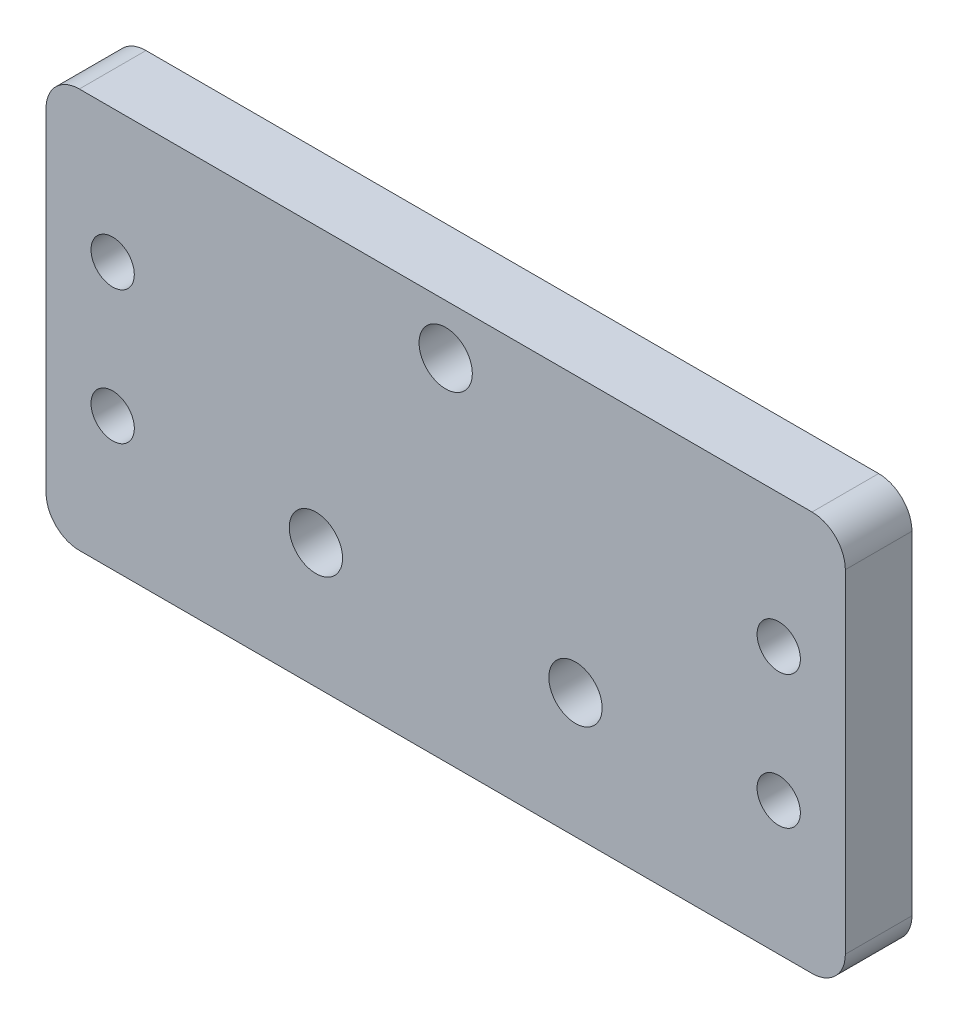
SolidWorks part; units mm, degrees
ref_plane "正面" through (0, 0, 0) normal (0, 0, 1) x (1, 0, 0)
ref_plane "平面" through (0, 0, 0) normal (0, 1, 0) x (1, 0, 0)
ref_plane "右側面" through (0, 0, 0) normal (1, 0, 0) x (0, 0, -1)
sketch "ｽｹｯﾁ1" plane through (0, 0, 0) normal (0, 0, 1) x (1, 0, 0)
  line L1 (0, 0) -> (120, 0)
  line L2 (0, 0) -> (0, 60)
  line L3 (0, 60) -> (120, 60)
  line L4 (120, 0) -> (120, 60)
  dimension "D1" = 60
  dimension "D2" = 120
extrude "ﾎﾞｽ - 押し出し1" add sketch "ｽｹｯﾁ1" along normal blind 10
sketch "ｽｹｯﾁ2" plane through (0, 0, 10) normal (0, 0, 1) x (1, 0, 0)
  line L0 (0, 30) -> (120, 30) construction
  line L1 (0, 60) -> (0, 0) construction
  line L2 (120, 0) -> (120, 60) construction
  line L3 (60, 0) -> (60, 60) construction
  line L4 (0, 0) -> (120, 0) construction
  line L5 (120, 60) -> (0, 60) construction
  circle A0 centre (10, 40) radius 3.25
  circle A1 centre (110, 40) radius 3.25
  circle A3 centre (110, 20) radius 3.25
  circle A4 centre (10, 20) radius 3.25
  point P18 (10.2137, 30)
  dimension "D4" = 6.5
  dimension "D1" = 10
  dimension "D2" = 10
  dimension "D3" = 10
  dimension "D5" = 10
extrude "ｶｯﾄ - 押し出し1" cut sketch "ｽｹｯﾁ2" against normal through all
sketch "ｽｹｯﾁ3" plane through (0, 0, 10) normal (0, 0, 1) x (1, 0, 0)
  line L0 (60, 0) -> (60, 60) construction
  line L1 (0, 0) -> (120, 0) construction
  line L2 (120, 60) -> (0, 60) construction
  line L3 (120, 30) -> (0, 30) construction
  line L4 (120, 0) -> (120, 60) construction
  line L5 (0, 60) -> (0, 0) construction
  line L6 (60, 30) -> (79.4856, 18.75) construction
  circle A0 centre (60, 52.5) radius 2.25
  circle A1 centre (79.4856, 18.75) radius 2.25
  circle A2 centre (40.5144, 18.75) radius 2.25
  point P14 (60, 30)
  dimension "D1" = 4.5
  dimension "D5" = 4.5
  dimension "D2" = 22.5
  dimension "D3" = 22.5
  dimension "D4" = 120
ref_point "点2"
extrude "ｶｯﾄ - 押し出し2" cut sketch "ｽｹｯﾁ3" against normal through all
sketch "ｽｹｯﾁ4" plane through (0, 0, 10) normal (0, 0, 1) x (1, 0, 0)
  circle A0 centre (60, 52.5) radius 4
  circle A1 centre (79.4856, 18.75) radius 4
  circle A2 centre (40.5144, 18.75) radius 4
  dimension "D1" = 8
extrude "ｶｯﾄ - 押し出し3" cut sketch "ｽｹｯﾁ4" against normal blind 6
fillet "ﾌｨﾚｯﾄ1" radius 5 4 edges at (120, 60, 5) (120, 0, 5) (0, 0, 5) (0, 60, 5)
